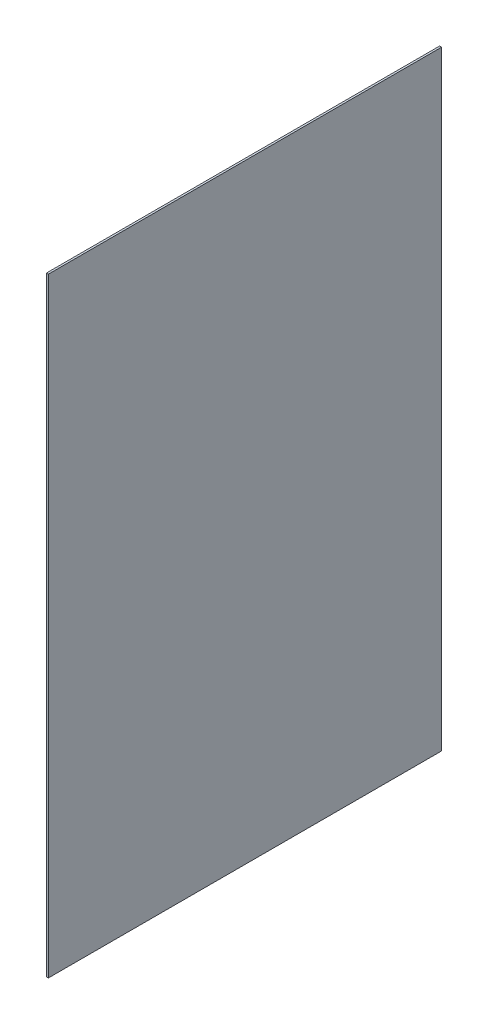
SolidWorks part; units mm, degrees
ref_plane "Front Plane" through (0, 0, 0) normal (0, 0, 1) x (1, 0, 0)
ref_plane "Top Plane" through (0, 0, 0) normal (0, 1, 0) x (1, 0, 0)
ref_plane "Right Plane" through (0, 0, 0) normal (1, 0, 0) x (0, 0, -1)
sketch "Sketch2" plane through (0, 0, 0) normal (1, 0, 0) x (0, 0, -1)
  line L1 (254, 393.7) -> (-254, 393.7)
  line L2 (254, 393.7) -> (254, -393.7)
  line L3 (254, -393.7) -> (-254, -393.7)
  line L4 (-254, 393.7) -> (-254, -393.7)
  line L5 (254, 393.7) -> (-254, -393.7) construction
  line L6 (254, -393.7) -> (-254, 393.7) construction
  point P0 (0, 0)
  dimension "D1" = 508
  dimension "D2" = 787.4
extrude "Boss-Extrude1" add sketch "Sketch2" along normal blind 2.54
